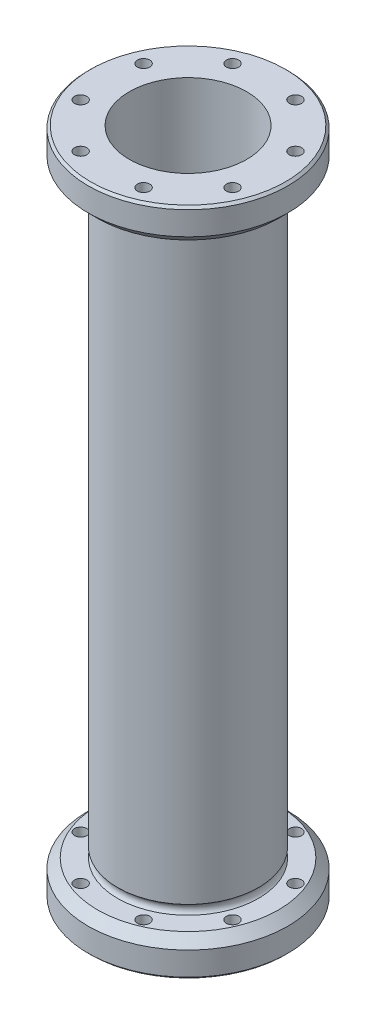
SolidWorks part; units mm, degrees
ref_plane "前基準面" through (0, 0, 0) normal (0, 0, 1) x (1, 0, 0)
ref_plane "上基準面" through (0, 0, 0) normal (0, 1, 0) x (1, 0, 0)
ref_plane "右基準面" through (0, 0, 0) normal (1, 0, 0) x (0, 0, -1)
sketch "草圖1" plane through (0, 0, 0) normal (0, 0, 1) x (1, 0, 0)
  line L0 (0, -1001.1352) -> (0, 48998.8648) construction
  line L1 (50, 0) -> (85, 0)
  line L2 (85, 0) -> (85, 30)
  line L3 (85, 30) -> (60, 30)
  line L4 (60, 30) -> (60, 540)
  line L5 (60, 540) -> (85, 540)
  line L6 (85, 540) -> (85, 570)
  line L7 (85, 570) -> (50, 570)
  line L8 (50, 570) -> (50, 0)
  dimension "D1" = 30
  dimension "D2" = 510
  dimension "D3" = 170
  dimension "D4" = 120
  dimension "D5" = 100
  dimension "D6" = 170
revolve "旋轉1" add sketch "草圖1" angle 360 about L0
sketch "草圖2" plane through (0, 0, 0) normal (0, 0, 1) x (1, 0, 0)
  line L0 (60, 30) -> (60, 540) construction
  line L1 (60, 540) -> (60, 532)
  line L2 (60, 38) -> (60, 30)
  line L3 (85, 30) -> (-85, 30) construction
  arc A0 (60, 540) -> (60, 532) centre (63, 536) ccw
  arc A1 (60, 38) -> (60, 30) centre (63, 34) ccw
  dimension "D1" = 5
  dimension "D2" = 8
revolve "除料-旋轉1" cut sketch "草圖2" angle 360 about axis through (0, -1001.1352, 0) along (0, -1, 0)
hole_wizard "M12x1.5 螺紋孔1" positions "草圖4" profile "草圖3" tap size "M12x1.5" standard "ISO" end condition through all
sketch "草圖4" plane through (0, 0, 0) normal (0, -1, 0) x (1, 0, 0)
  line L0 (0, 0) -> (-85, 0) construction
  line L1 (0, 0) -> (-64.6716, 26.7878) construction
  circle A0 centre (0, 0) radius 85 construction
  circle A1 centre (0, 0) radius 70 construction
  point P0 (-64.6716, 26.7878)
  dimension "D1" = 140
  dimension "D2" = 22.5
sketch "草圖3" plane through (-64.6716, 0, 26.7878) normal (1, 0, 0) x (0, 0, -1)
  line L0 (0, 0) -> (0, 570)
  line L1 (0, 570) -> (5.25, 570)
  line L2 (5.25, 570) -> (5.25, 0)
  line L5 (5.25, 0) -> (0, 0)
  line L11 (0, -6.35) -> (0, 107.95) construction
  dimension "貫穿螺孔鑽直徑" = 10.5
  dimension "貫穿螺孔鑽深度" = 570
cosmetic thread "鑽孔螺紋1" parameters "D2"=12
pattern_circular "環狀複製排列1" count 8 over 360 about axis through (0, 0, 0) along (0, 1, 0) of "M12x1.5 螺紋孔1"
chamfer "導角1" distance 8 angle 45 2 edges at (0, 540, -85) (0, 30, -85)
chamfer "導角2" distance 2 angle 45 2 edges at (0, 570, -85) (0, 0, -85)
